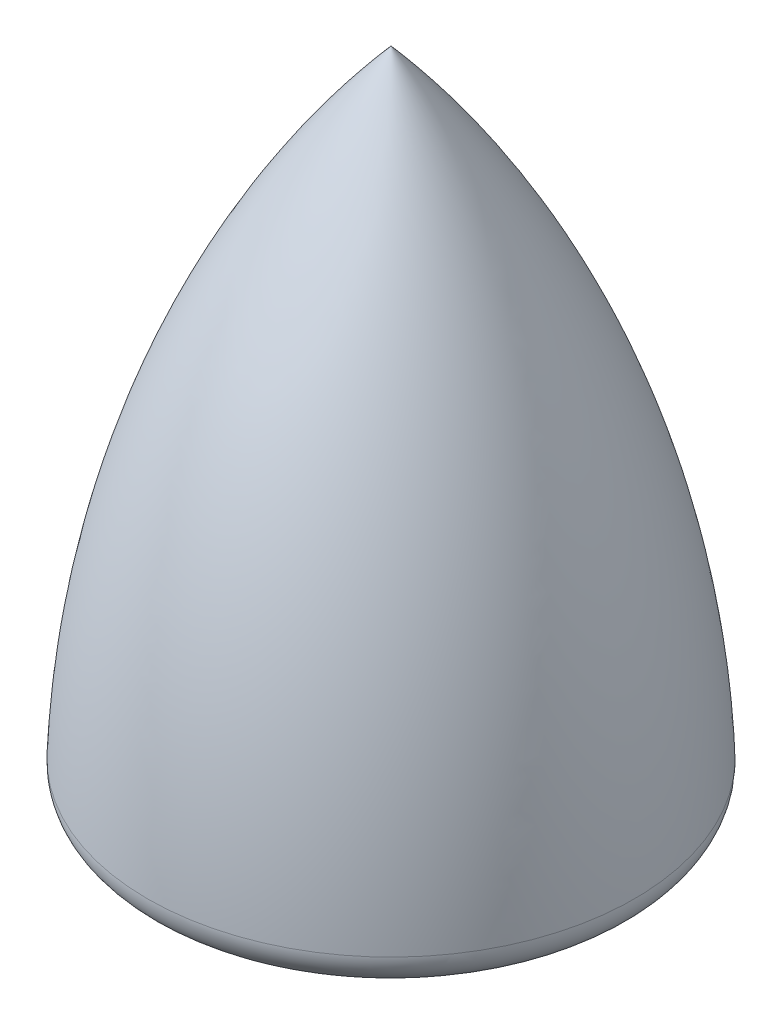
SolidWorks part; units mm, degrees
ref_plane "Front Plane" through (0, 0, 0) normal (0, 0, 1) x (1, 0, 0)
ref_plane "Top Plane" through (0, 0, 0) normal (0, 1, 0) x (1, 0, 0)
ref_plane "Right Plane" through (0, 0, 0) normal (1, 0, 0) x (0, 0, -1)
sketch "Sketch2" plane through (0, 0, 0) normal (1, 0, 0) x (0, 0, -1)
  line L0 (0, 9.5715) -> (0, -10.4285) construction
  line L1 (0, -10.4285) -> (7.5, -10.4285)
  line L2 (0, 9.5715) -> (0, -10.4285)
  arc A0 (0, 9.5715) -> (7.5, -10.4285) centre (-23.2972, -10.5712) cw
  dimension "D1" = 20
  dimension "D2" = 7.5
revolve "Revolve1" add sketch "Sketch2" angle 360 about L0
fillet "Fillet5" radius 1 1 edges at (0, -10.4285, 7.5)
sketch "Sketch4" plane through (0, -10.4285, 0) normal (0, -1, 0) x (1, 0, 0)
  circle A0 centre (0, 0) radius 2.5
  dimension "D1" = 5
extrude "Cut-Extrude1" cut sketch "Sketch4" against normal blind 12
